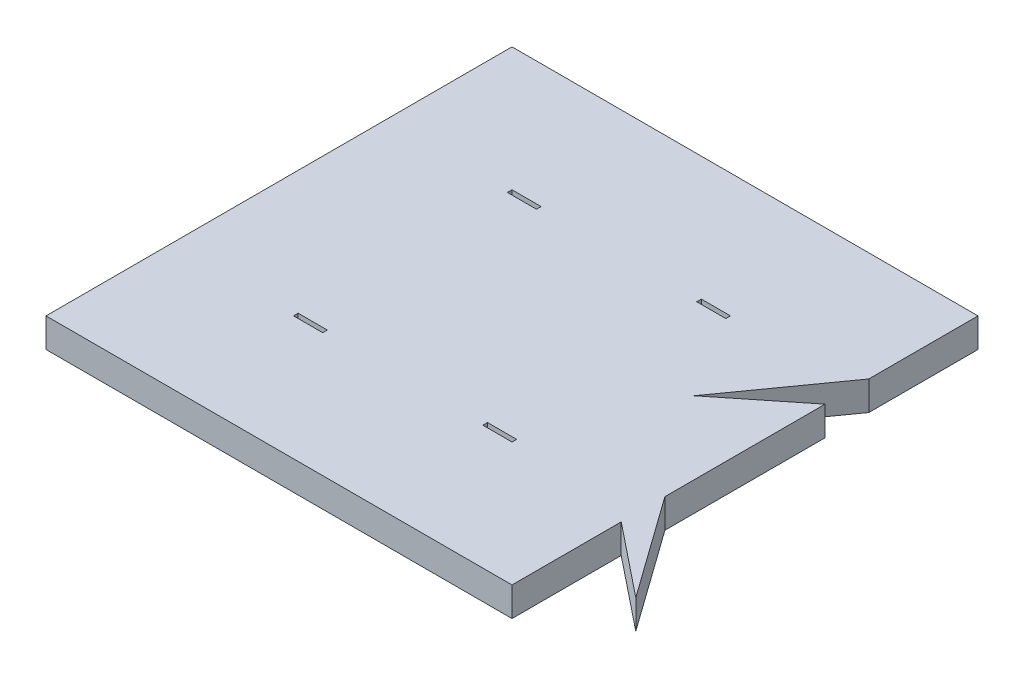
SolidWorks part; units mm, degrees
ref_plane "Front Plane" through (0, 0, 0) normal (0, 0, 1) x (1, 0, 0)
ref_plane "Top Plane" through (0, 0, 0) normal (0, 1, 0) x (1, 0, 0)
ref_plane "Right Plane" through (0, 0, 0) normal (1, 0, 0) x (0, 0, -1)
sketch "Sketch1" plane through (0, 0, 0) normal (0, 1, 0) x (1, 0, 0)
  line L0 (320, 245) -> (270, 175)
  line L1 (0, 0) -> (320, 0)
  line L2 (0, 0) -> (0, 320)
  line L3 (0, 320) -> (320, 320)
  line L4 (320, 0) -> (320, 75)
  line L5 (270, 175) -> (320, 215)
  line L6 (320, 105) -> (370, 35)
  line L7 (370, 35) -> (320, 75)
  line L8 (320, 245) -> (320, 320)
  line L9 (320, 105) -> (320, 215)
  dimension "D1" = 320
  dimension "D2" = 320
  dimension "D3" = 75
  dimension "D4" = 75
  dimension "D5" = 370
  dimension "D6" = 270
  dimension "D7" = 110
  dimension "D8" = 30
  dimension "D9" = 40
  dimension "D10" = 40
extrude "Boss-Extrude1" add sketch "Sketch1" along normal blind 20
sketch "Sketch2" plane through (0, 20, 0) normal (0, 1, 0) x (1, 0, 0)
  line L0 (320, 320) -> (0, 320) construction
  line L1 (85, 85) -> (235, 85) construction
  line L2 (85, 85) -> (85, 235) construction
  line L3 (85, 235) -> (235, 235) construction
  line L4 (235, 85) -> (235, 235) construction
  line L5 (0, 320) -> (0, 0) construction
  line L7 (235, 235) -> (215, 235)
  line L8 (235, 235) -> (235, 231.825)
  line L9 (235, 231.825) -> (215, 231.825)
  line L10 (215, 235) -> (215, 231.825)
  line L11 (85, 235) -> (105, 235)
  line L12 (85, 235) -> (85, 231.825)
  line L13 (85, 231.825) -> (105, 231.825)
  line L14 (105, 235) -> (105, 231.825)
  line L15 (85, 85) -> (105, 85)
  line L16 (85, 85) -> (85, 88.175)
  line L17 (85, 88.175) -> (105, 88.175)
  line L18 (105, 85) -> (105, 88.175)
  line L19 (235, 85) -> (215, 85)
  line L20 (235, 85) -> (235, 88.175)
  line L21 (235, 88.175) -> (215, 88.175)
  line L22 (215, 85) -> (215, 88.175)
  point P21 (154.6482, 107.2736)
  point P22 (150.1714, 126.7768)
  point P23 (138.472, 129.5479)
  dimension "D1" = 150
  dimension "D2" = 150
  dimension "D3" = 85
  dimension "D4" = 85
  dimension "D5" = 20
  dimension "D6" = 3.175
extrude "Cut-Extrude2" cut sketch "Sketch2" against normal through all
